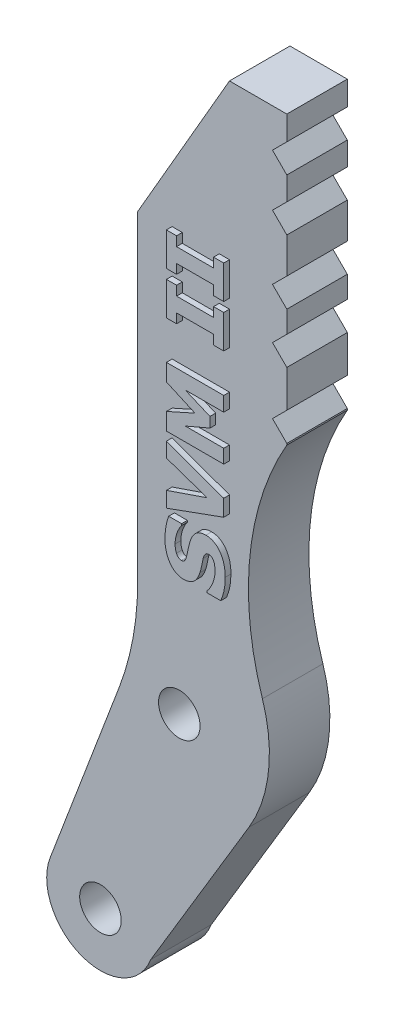
SolidWorks part; units mm, degrees
ref_plane "Front Plane" through (0, 0, 0) normal (0, 0, 1) x (1, 0, 0)
ref_plane "Top Plane" through (0, 0, 0) normal (0, 1, 0) x (1, 0, 0)
ref_plane "Right Plane" through (0, 0, 0) normal (1, 0, 0) x (0, 0, -1)
sketch "Sketch1" plane through (0, 0, 0) normal (0, 0, 1) x (1, 0, 0)
  line L0 (6.985, 18.415) -> (0, 0) construction
  line L3 (20.9869, 18.415) -> (16.51, 18.415) construction
  line L10 (4.1556, 18.415) -> (-12.6376, 18.415) construction
  line L12 (20.9869, 18.415) -> (16.51, 18.415) construction
  line L15 (0, 0) -> (6.985, 18.415) construction
  line L19 (-1.2084, 47.3246) -> (-1.2084, 10.2427)
  line L21 (0, 0) -> (6.985, 18.415) construction
  line L30 (16.51, 69.215) -> (16.51, 43.815)
  line L31 (0, 0) -> (6.985, 18.415) construction
  line L36 (11.43, 18.415) -> (-26.9598, 18.415) construction
  line L38 (15.0503, 0.635) -> (5.4573, 0.635) construction
  line L40 (0, 0) -> (6.985, 18.415) construction
  line L43 (1.7286, 0.635) -> (-5.0402, 0.635) construction
  line L44 (0, 0) -> (6.985, 18.415) construction
  line L45 (-4.4529, 1.689) -> (-1.2084, 10.2427)
  line L47 (16.51, 18.415) -> (4.4529, -1.689)
  line L48 (16.51, 69.215) -> (11.43, 69.215)
  line L49 (11.43, 69.215) -> (-1.2084, 47.3246)
  circle A8 centre (0, 0) radius 1.8415
  circle A9 centre (6.985, 18.415) radius 1.8415
  arc A27 (-4.4529, 1.689) -> (4.4529, -1.689) centre (0, 0) ccw
  arc A28 (16.51, 43.815) -> (16.51, 18.415) centre (38.507, 31.115) ccw
  point P0 (11.2903, 20.32)
  point P3 (5.08, 13.97)
  point P6 (4.9403, 14.2021)
  point P7 (5.08, 13.97)
  point P17 (3.4925, 12.3825)
  point P21 (5.8737, 13.97)
  point P22 (3.4925, 12.3825)
  point P23 (3.4925, 9.2075)
  dimension "D3" = 6.985
  dimension "D4" = 25.4
  dimension "D5" = 18.415
  dimension "D1" = 3.683
  dimension "D2" = 3.683
  dimension "D10" = 5.08
  dimension "D8" = 4.7625
  dimension "D12" = 50.8
  dimension "D9" = 25.4
extrude "Boss-Extrude1" add sketch "Sketch1" along normal blind 5.08 and the other way blind 0.2784
sketch "Sketch2" plane through (0, 0, -0.2784) normal (0, 0, -1) x (-1, 0, 0)
  line L0 (-16.51, 56.7826) -> (-15.24, 55.5126)
  line L1 (-16.51, 68.6939) -> (-15.24, 68.6939)
  line L2 (-16.51, 68.6939) -> (-16.51, 43.9464)
  line L4 (-15.24, 68.6939) -> (-15.24, 45.2164)
  line L5 (-15.24, 55.5126) -> (-16.51, 54.2426)
  line L6 (-16.51, 52.3146) -> (-15.24, 51.0446)
  line L7 (-16.51, 43.815) -> (-16.51, 69.215) construction
  line L8 (-15.24, 51.0446) -> (-16.51, 49.7746)
  line L13 (-15.24, 45.2164) -> (-16.51, 43.9464)
  line L14 (-16.51, 67.0788) -> (-15.24, 65.8088)
  line L15 (-15.24, 65.8088) -> (-16.51, 64.5388)
  line L16 (-16.51, 62.4746) -> (-15.24, 61.2046)
  line L17 (-15.24, 61.2046) -> (-16.51, 59.9346)
  line L18 (-16.51, 46.4864) -> (-15.24, 45.2164)
  dimension "D1" = 1.27
extrude "Cut-Extrude1" cut sketch "Sketch2" against normal through all both and the other way through all
fillet "Fillet2" radius 12.7 2 edges at (-1.2084, 10.2427, 2.4008) (16.51, 18.415, 2.4008)
sketch "Sketch3" plane through (0, 0, 5.08) normal (0, 0, 1) x (1, 0, 0)
  line L0 (11.43, 88.265) -> (11.43, -1.7652) construction
  line L1 (16.51, 67.0788) -> (16.51, 69.215) construction
  text T0 "<b>SVM II</b>" font "Verdana" height 5.08
  dimension "D1" = 5.08
extrude "Boss-Extrude2" add sketch "Sketch3" along normal blind 0.508
sketch "Sketch4" plane through (0, 0, 5.08) normal (0, 0, 1) x (1, 0, 0)
  line L1 (3.302, 55.1369) -> (-1.2084, 55.1369)
  line L2 (3.302, 55.1369) -> (3.302, 22.1338)
  line L4 (-1.2084, 55.1369) -> (-1.2084, 24.765)
  line L5 (-1.2084, 47.3246) -> (-1.2084, 12.5704) construction
  line L6 (-4.4529, 1.689) -> (2.5321, 20.104)
  line L10 (16.51, 67.0788) -> (16.51, 69.215) construction
  line L11 (-1.2084, 24.765) -> (-11.7572, 6.5479)
  line L12 (-11.7572, 6.5479) -> (-4.4529, 1.689)
  line L13 (2.5321, 20.104) -> (3.302, 22.1338)
  line L14 (11.43, 69.215) -> (-1.2084, 47.3246) construction
  point P4 (0, 0)
  dimension "D1" = 13.208
extrude "Cut-Extrude3" cut sketch "Sketch4" against normal through all both and the other way through all
fillet "Fillet3" radius 25.4 1 edges at (3.302, 22.1338, 2.4008)
